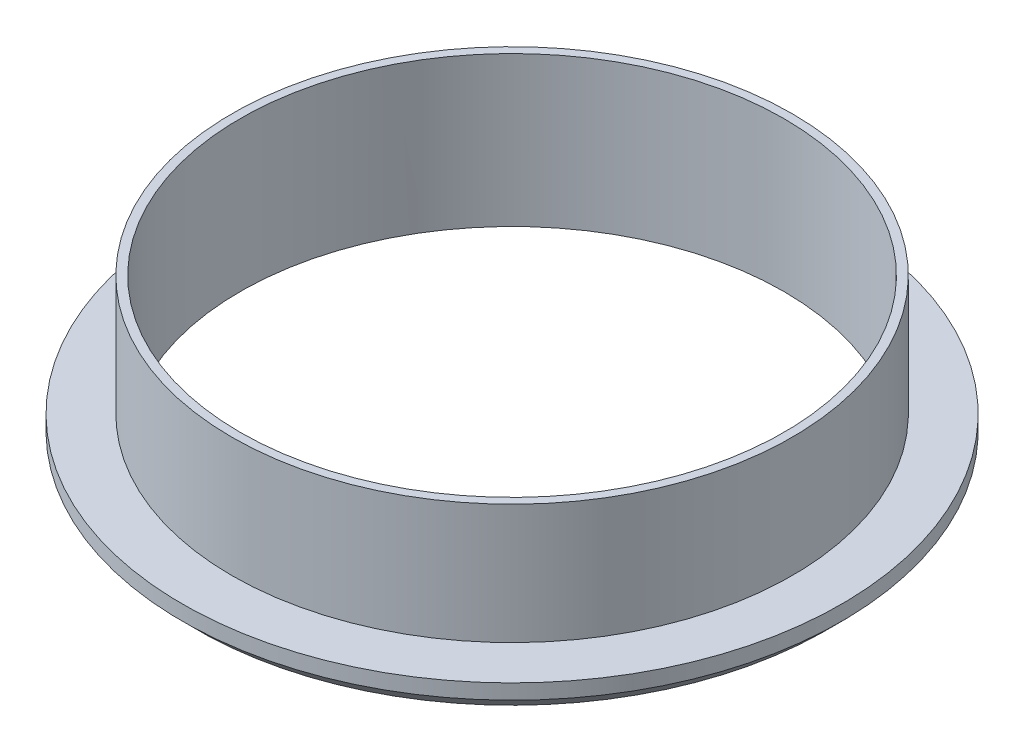
SolidWorks part; units mm, degrees
ref_plane "Front Plane" through (0, 0, 0) normal (0, 0, 1) x (1, 0, 0)
ref_plane "Top Plane" through (0, 0, 0) normal (0, 1, 0) x (1, 0, 0)
ref_plane "Right Plane" through (0, 0, 0) normal (1, 0, 0) x (0, 0, -1)
sketch "Sketch1" plane through (0, 0, 0) normal (0, 1, 0) x (1, 0, 0)
  circle A0 centre (0, 0) radius 14.8463
  circle A1 centre (0, 0) radius 14.4018
  dimension "D1" = 28.8036
  dimension "D2" = 29.6926
extrude "Boss-Extrude1" add sketch "Sketch1" along normal blind 6.35
sketch "Sketch2" plane through (0, 0, 0) normal (0, -1, 0) x (1, 0, 0)
  circle A0 centre (0, 0) radius 17.4625
  circle A1 centre (0, 0) radius 14.4018 construction
  circle A2 centre (0, 0) radius 14.4018
  dimension "D1" = 34.925
extrude "Boss-Extrude2" add sketch "Sketch2" along normal blind 1.5875
chamfer "Chamfer2" distance 0.7937 angle 45 1 edges at (0, -1.5875, -17.4625)
